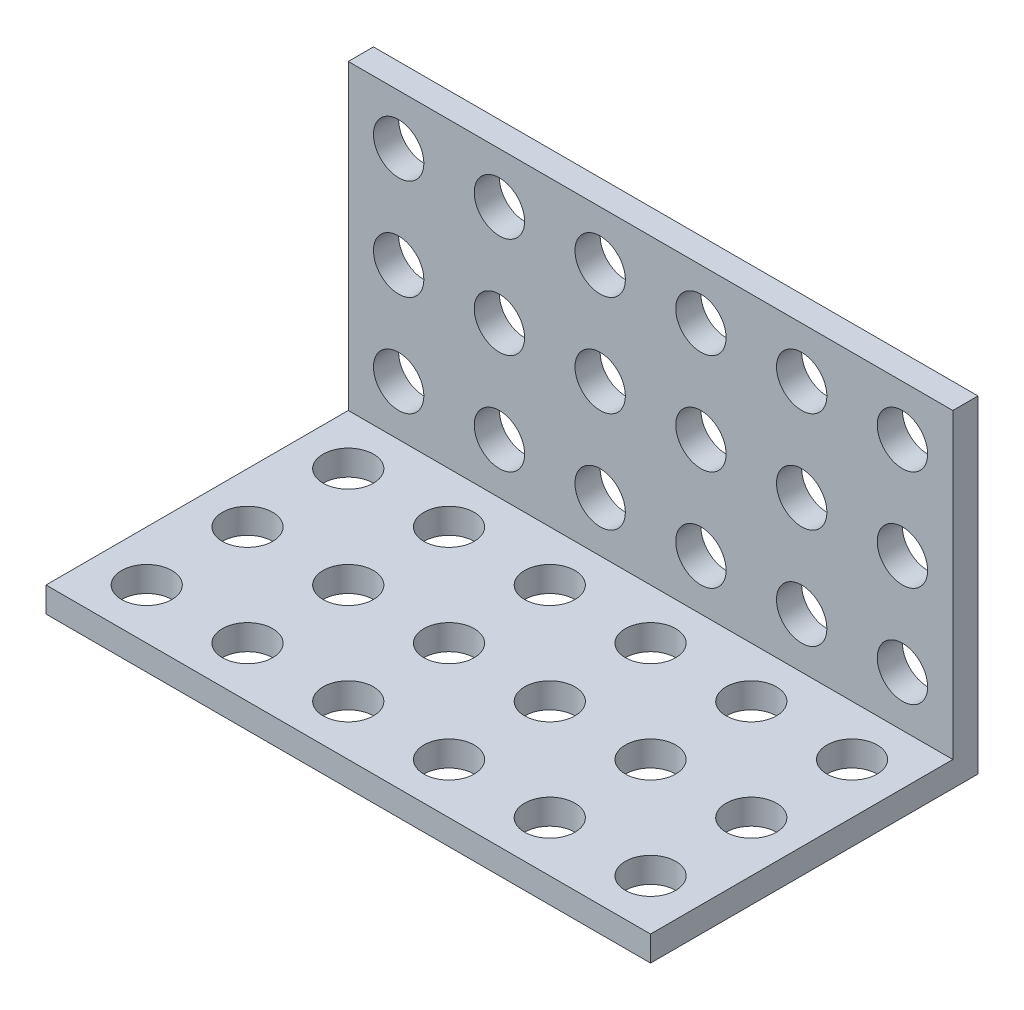
SolidWorks part; units mm, degrees
ref_plane "Front" through (0, 0, 0) normal (0, 0, 1) x (1, 0, 0)
ref_plane "Top" through (0, 0, 0) normal (0, 1, 0) x (1, 0, 0)
ref_plane "Right" through (0, 0, 0) normal (1, 0, 0) x (0, 0, -1)
sketch "草图1" plane through (0, 0, 0) normal (1, 0, 0) x (0, 0, -1)
  line L0 (0, 0) -> (-26, 0)
  line L1 (-26, 0) -> (-26, 2)
  line L2 (-26, 2) -> (-2, 2)
  line L3 (-2, 2) -> (-2, 26)
  line L4 (-2, 26) -> (0, 26)
  line L5 (0, 26) -> (0, 0)
extrude "凸台-拉伸1" add sketch "草图1" along normal blind 48
sketch "草图2" plane through (0, 0, 2) normal (0, 0, 1) x (1, 0, 0)
  line L0 (48, 26) -> (0, 26) construction
  line L1 (0, 26) -> (0, 2) construction
  circle A0 centre (4, 22) radius 2
  circle A1 centre (4, 14) radius 2
  circle A2 centre (4, 6) radius 2
  circle A3 centre (12, 22) radius 2
  circle A4 centre (12, 14) radius 2
  circle A5 centre (12, 6) radius 2
  circle A6 centre (20, 22) radius 2
  circle A7 centre (20, 14) radius 2
  circle A8 centre (20, 6) radius 2
  circle A9 centre (28, 22) radius 2
  circle A10 centre (28, 14) radius 2
  circle A11 centre (28, 6) radius 2
  circle A12 centre (36, 22) radius 2
  circle A13 centre (36, 14) radius 2
  circle A14 centre (36, 6) radius 2
  circle A15 centre (44, 22) radius 2
  circle A16 centre (44, 14) radius 2
  circle A17 centre (44, 6) radius 2
  dimension "D1" = 4
  dimension "D2" = 4
  dimension "D3" = 3
  dimension "D4" = 6
extrude "切除-拉伸1" cut sketch "草图2" against normal blind 48
sketch "草图3" plane through (0, 2, 0) normal (0, 1, 0) x (1, 0, 0)
  line L0 (0, -2) -> (0, -26) construction
  line L1 (48, -26) -> (0, -26) construction
  circle A0 centre (4, -22) radius 2
  circle A1 centre (4, -14) radius 2
  circle A2 centre (4, -6) radius 2
  circle A3 centre (12, -6) radius 2
  circle A4 centre (12, -14) radius 2
  circle A5 centre (12, -22) radius 2
  circle A6 centre (20, -6) radius 2
  circle A7 centre (20, -14) radius 2
  circle A8 centre (20, -22) radius 2
  circle A9 centre (28, -6) radius 2
  circle A10 centre (28, -14) radius 2
  circle A11 centre (28, -22) radius 2
  circle A12 centre (36, -6) radius 2
  circle A13 centre (36, -14) radius 2
  circle A14 centre (36, -22) radius 2
  circle A15 centre (44, -6) radius 2
  circle A16 centre (44, -14) radius 2
  circle A17 centre (44, -22) radius 2
  dimension "D1" = 4
  dimension "D2" = 4
  dimension "D3" = 3
  dimension "D4" = 6
extrude "切除-拉伸3" cut sketch "草图3" against normal blind 48
